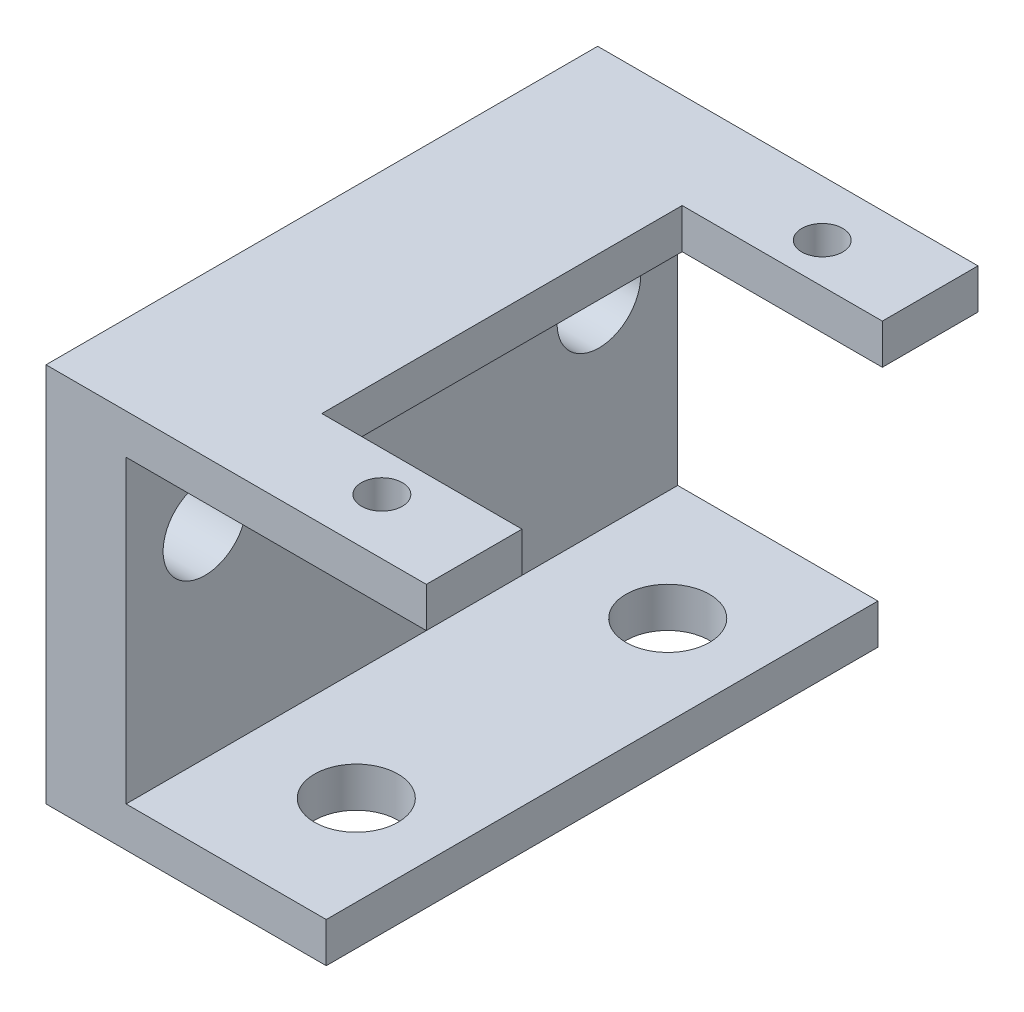
SolidWorks part; units mm, degrees
ref_plane "Front Plane" through (0, 0, 0) normal (0, 0, 1) x (1, 0, 0)
ref_plane "Top Plane" through (0, 0, 0) normal (0, 1, 0) x (1, 0, 0)
ref_plane "Right Plane" through (0, 0, 0) normal (1, 0, 0) x (0, 0, -1)
sketch "Sketch1" plane through (0, 0, 0) normal (0, 0, 1) x (1, 0, 0)
  line L1 (0, 0) -> (17.78, 0)
  line L2 (0, 0) -> (0, 2.54)
  line L3 (0, 2.54) -> (17.78, 2.54)
  line L4 (17.78, 0) -> (17.78, 2.54)
  line L5 (0, 2.54) -> (5.08, 2.54)
  line L6 (0, 2.54) -> (0, 21.59)
  line L7 (0, 21.59) -> (5.08, 21.59)
  line L8 (5.08, 2.54) -> (5.08, 21.59)
  line L9 (0, 21.59) -> (24.13, 21.59)
  line L10 (0, 21.59) -> (0, 24.13)
  line L11 (0, 24.13) -> (24.13, 24.13)
  line L12 (24.13, 21.59) -> (24.13, 24.13)
  dimension "D1" = 5.08
  dimension "D2" = 12.7
  dimension "D3" = 19.05
  dimension "D4" = 2.54
  dimension "D5" = 2.54
  dimension "D6" = 19.05
extrude "Boss-Extrude1" add sketch "Sketch1" along normal blind 35 contours L9 L12 L11 L10 L7 | L2 L1 L4 L3
hole_wizard "Ø5.0mm Dowel Hole1" positions "Sketch2" profile "Sketch3" hole size "Ø5.0" standard "ANSI Metric" end condition through all
sketch "Sketch2" plane through (5.08, 0, 0) normal (1, 0, 0) x (0, 0, -1)
  line L3 (-35, 2.54) -> (0, 2.54) construction
  line L6 (-30, 15.24) -> (-5, 15.24) construction
  line L8 (-35, 0) -> (0, 0) construction
  point P0 (-30, 15.24)
  point P2 (-5, 15.24)
  point P30 (-17.5, 0)
  point P31 (-17.5, 15.24)
  dimension "D1" = 25
  dimension "D3" = 12.7
sketch "Sketch3" plane through (5.08, 15.24, 30) normal (0, 1, 0) x (0, 0, -1)
  line L0 (0, 0) -> (0, 5.08)
  line L1 (0, 5.08) -> (2.65, 5.08)
  line L2 (2.65, 5.08) -> (2.65, 0)
  line L5 (2.65, 0) -> (0, 0)
  line L11 (0, -6.35) -> (0, 107.95) construction
  dimension "Thru Hole Dia." = 5.3
  dimension "Thru Hole Depth" = 5.08
hole_wizard "Ø5.0mm Dowel Hole2" positions "Sketch4" profile "Sketch5" hole size "Ø5.0" standard "ANSI Metric"
sketch "Sketch4" plane through (0, 2.54, 0) normal (0, 1, 0) x (1, 0, 0)
  line L2 (12.065, 0) -> (12.065, -35) construction
  line L3 (0, 0) -> (24.13, 0) construction
  line L4 (0, -35) -> (24.13, -35) construction
  point P0 (12.065, -27.38)
  point P2 (12.065, -7.62)
  point P16 (12.065, 0)
  point P18 (12.065, -35)
  dimension "D1" = 7.62
  dimension "D2" = 7.62
sketch "Sketch5" plane through (12.065, 2.54, 27.38) normal (1, 0, 0) x (0, 0, 1)
  line L0 (0, 0) -> (0, 2.54)
  line L1 (0, 2.54) -> (2.65, 2.54)
  line L2 (2.65, 2.54) -> (2.65, 0)
  line L5 (2.65, 0) -> (0, 0)
  line L11 (0, -6.35) -> (0, 107.95) construction
  dimension "Thru Hole Dia." = 5.3
  dimension "Thru Hole Depth" = 2.54
sketch "Sketch6" plane through (0, 24.13, 0) normal (0, 1, 0) x (1, 0, 0)
  line L0 (24.13, -35) -> (24.13, 0) construction
  line L1 (24.13, -6.07) -> (11.43, -6.07)
  line L2 (24.13, -6.07) -> (24.13, -28.93)
  line L3 (24.13, -28.93) -> (11.43, -28.93)
  line L4 (11.43, -6.07) -> (11.43, -28.93)
  line L5 (0, 0) -> (24.13, 0) construction
  line L6 (0, -35) -> (24.13, -35) construction
  line L9 (17.78, -6.07) -> (17.78, 0) construction
  line L10 (17.78, -28.93) -> (17.78, -35) construction
  dimension "D2" = 12.7
  dimension "D1" = 22.86
extrude "Cut-Extrude1" cut sketch "Sketch6" against normal up to next contours L2 L1 L4 L3
hole_wizard "M2 Clearance Hole1" positions "Sketch7" profile "Sketch8" hole size "M2" standard "ANSI Metric"
sketch "Sketch7" plane through (0, 24.13, 0) normal (0, 1, 0) x (1, 0, 0)
  line L0 (17.78, -28.93) -> (17.78, -35) construction
  line L1 (17.78, -6.07) -> (17.78, 0) construction
  line L2 (11.43, -6.07) -> (11.43, -28.93) construction
  point P0 (17.78, -31.47)
  point P4 (17.78, -3.53)
  point P13 (11.43, -17.5)
  dimension "D1" = 13.97
  dimension "D2" = 13.97
sketch "Sketch8" plane through (17.78, 24.13, 31.47) normal (1, 0, 0) x (0, 0, 1)
  line L0 (0, 0) -> (0, 2.54)
  line L1 (0, 2.54) -> (1.3, 2.54)
  line L2 (1.3, 2.54) -> (1.3, 0)
  line L5 (1.3, 0) -> (0, 0)
  line L11 (0, -6.35) -> (0, 107.95) construction
  dimension "Thru Hole Dia." = 2.6
  dimension "Thru Hole Depth" = 2.54
equation "\"wall thicc\"= 2.5mm"
equation "\"press fit\"= 0.3mm"
equation "\"shaft thick\"= 5mm + \"press fit\""
equation "\"D1@Sketch1\"=\"wall thicc\"*2"
equation "\"D4@Sketch1\"=\"wall thicc\""
equation "\"D5@Sketch1\"=\"wall thicc\""
equation "\"servo width\"= 22.5mm"
equation "\"D1@Sketch6\"=\"servo width\"+\"press fit\""
equation "\"servo length\"= 12.5mm"
equation "\"D2@Sketch6\"=\"servo length\"+\"press fit\""
equation "\"servo hole spacing\"= 13.9mm"
equation "\"D1@Sketch7\"=\"servo hole spacing\""
equation "\"D2@Sketch7\"=\"servo hole spacing\""
